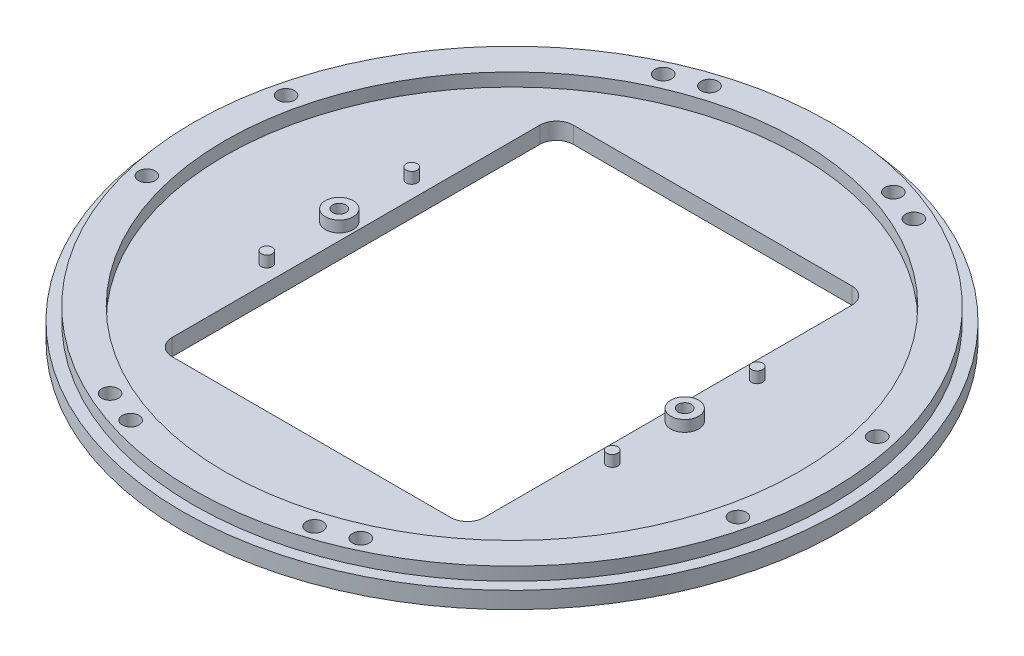
SolidWorks part; units mm, degrees
material "6061 合金"
ref_plane "前视基准面" through (0, 0, 0) normal (0, 0, 1) x (1, 0, 0)
ref_plane "上视基准面" through (0, 0, 0) normal (0, 1, 0) x (1, 0, 0)
ref_plane "右视基准面" through (0, 0, 0) normal (1, 0, 0) x (0, 0, -1)
sketch "草图1" plane through (0, 0, 0) normal (0, 0, 1) x (1, 0, 0)
  line L0 (0, 0) -> (-26746.8927, 0) construction
  line L1 (0, 0) -> (0, 26746.8927) construction
  line L2 (51.5, 2.35) -> (51.5, -3)
  line L3 (51.5, -3) -> (59.15, -3)
  line L4 (59.15, -3) -> (59.15, 0)
  line L5 (59.15, 0) -> (57.15, 0)
  line L6 (57.15, 0) -> (57.15, 2.35)
  line L7 (57.15, 2.35) -> (51.5, 2.35)
  dimension "D1" = 114.3
  dimension "D2" = 2
  dimension "D3" = 3
  dimension "D4" = 2.35
  dimension "D5" = 103
revolve "旋转1" add sketch "草图1" angle 360 about L1
sketch "草图3" plane through (0, 2.35, 0) normal (0, 1, 0) x (1, 0, 0)
  line L0 (0, -0.8566) -> (0, -50000.8566) construction
  line L1 (0, 0) -> (-50000, 0) construction
  line L2 (-22.5, 49.6387) -> (-22.5, -49.6387) construction
  line L3 (-16.5, 51.9423) -> (-16.5, -51.9423) construction
  circle A0 centre (0, 0) radius 54.5 construction
  circle A1 centre (-16.5, -51.9423) radius 1.5
  circle A2 centre (-22.5, -49.6387) radius 1.5
  circle A3 centre (-22.5, 49.6387) radius 1.5
  circle A4 centre (-16.5, 51.9423) radius 1.5
  circle A5 centre (16.5, 51.9423) radius 1.5
  circle A6 centre (22.5, 49.6387) radius 1.5
  circle A7 centre (22.5, -49.6387) radius 1.5
  circle A8 centre (16.5, -51.9423) radius 1.5
  point P10 (-22.5, 0)
  point P13 (-16.5, 0)
  dimension "D1" = 109
  dimension "D4" = 3
  dimension "D2" = 22.5
  dimension "D3" = 6
extrude "切除-拉伸1" cut sketch "草图3" against normal through all
sketch "草图2" plane through (0, -3, 0) normal (0, -1, 0) x (1, 0, 0)
  line L0 (0, 0) -> (0, 50000) construction
  line L1 (0, 0) -> (-50000, 0) construction
  line L2 (-28, 36) -> (-28, -36)
  line L3 (28, 36) -> (28, -36)
  line L4 (-28, 36) -> (28, 36)
  line L5 (-28, -36) -> (28, -36)
  circle A0 centre (0, 0) radius 51.5 construction
  circle A1 centre (0, 0) radius 51.5
  circle A3 centre (0, 0) radius 44 construction
  point P57 (0, 0)
  dimension "D4" = 36
  dimension "D2" = 88
  dimension "D1" = 28
extrude "凸台-拉伸1" add sketch "草图2" against normal blind 3
sketch "草图4" plane through (0, 0, 0) normal (0, 1, 0) x (1, 0, 0)
  line L0 (0.4768, 0) -> (50000.4768, 0) construction
  line L1 (0, -0.6791) -> (0, -50000.6791) construction
  circle A0 centre (0, 0) radius 50.1 construction
  circle A1 centre (45, 0) radius 5.1 construction
  circle A2 centre (45, 0) radius 5.7 construction
  circle A3 centre (0, 0) radius 39.3 construction
  circle A4 centre (31, -13) radius 1
  circle A6 centre (-31, -13) radius 1
  circle A7 centre (-31, 13) radius 1
  circle A8 centre (31, 13) radius 1
  circle A9 centre (31, 0) radius 2.5
  circle A10 centre (-31, 0) radius 2.5
  dimension "D1" = 100.2
  dimension "D2" = 10.2
  dimension "D3" = 11.4
  dimension "D4" = 2
  dimension "D5" = 31
  dimension "D6" = 13
  dimension "D7" = 5
  dimension "D8" = 78.6
extrude "凸台-拉伸2" add sketch "草图4" along normal blind 2
sketch "草图5" plane through (0, 2, 0) normal (0, 1, 0) x (1, 0, 0)
  circle A0 centre (31, 0) radius 1.2
  circle A1 centre (-31, 0) radius 1.2
  dimension "D1" = 2.4
extrude "切除-拉伸2" cut sketch "草图5" against normal through all
cosmetic thread "装饰螺纹线1" parameters "D1"=5, "D2"=3
cosmetic thread "装饰螺纹线2" parameters "D1"=5, "D2"=3
sketch "草图6" plane through (0, 0, 0) normal (0, 0, 1) x (1, 0, 0)
  line L0 (0, 0) -> (0, -39.9563) construction
  line L1 (57.15, 0) -> (-57.15, 0) construction
  line L2 (-32, -3) -> (-32, -20.2648) construction
  line L3 (-59.15, -3) -> (59.15, -3) construction
  line L4 (30.5, -3) -> (30.5, -25.0635) construction
  line L5 (-32, -3) -> (-32, -11)
  line L6 (-32, -11) -> (-52, -11)
  line L7 (-52, -11) -> (-59.15, -6)
  line L8 (-59.15, -6) -> (-59.15, -3)
  line L9 (-59.15, -3) -> (-32, -3)
  line L10 (30.5, -11) -> (50.5, -11)
  line L11 (50.5, -11) -> (59.15, -6)
  line L12 (59.15, -6) -> (59.15, -3)
  line L13 (59.15, -3) -> (30.5, -3)
  line L14 (30.5, -3) -> (30.5, -11)
  dimension "D1" = 32
  dimension "D2" = 30.5
  dimension "D3" = 8
  dimension "D4" = 3
  dimension "D5" = 20
sketch "草图8" plane through (0, 0, 0) normal (1, 0, 0) x (0, 0, -1)
  line L0 (0, 0) -> (0, -8.5) construction
  line L1 (59.15, 0) -> (-59.15, 0) construction
  line L2 (-59.15, -3) -> (59.15, -3) construction
  circle A0 centre (0, -8.5) radius 1.6
  dimension "D1" = 5.5
  dimension "D2" = 3.2
sketch "草图9" plane through (0, -3, 0) normal (0, -1, 0) x (1, 0, 0)
  circle A0 centre (-31, 0) radius 1.2 construction
  circle A1 centre (31, 0) radius 1.2 construction
  circle A2 centre (-31, 0) radius 1.2
  circle A3 centre (31, 0) radius 1.2
sketch "草图14" plane through (0, 0, 0) normal (0, 1, 0) x (1, 0, 0)
  line L0 (35.5031, -5.3746) -> (35.5031, 4.6254) construction
  circle A0 centre (35.5031, -5.3746) radius 2.5
  circle A1 centre (35.5031, 4.6254) radius 2.5
  circle A2 centre (35.5031, -0.3746) radius 2.5
  dimension "D1" = 5
fillet "圆角2" radius 3 4 edges at (-28, -1.5, 36) (28, -1.5, 36) (28, -1.5, -36) (-28, -1.5, -36)
sketch "草图11" plane through (0, -3, 0) normal (0, -1, 0) x (1, 0, 0)
  line L0 (0, 0) -> (-50000, 0) construction
  line L1 (0, 0) -> (0, 50000) construction
  circle A0 centre (0, 0) radius 54.5 construction
  circle A1 centre (-53.0471, 12.5) radius 1.5
  circle A2 centre (-53.0471, 12.5) radius 3 construction
  circle A3 centre (-40.0156, 37) radius 1.5 construction
  circle A5 centre (53.0471, 12.5) radius 1.5
  circle A7 centre (53.0471, -12.5) radius 1.5
  circle A10 centre (-53.0471, -12.5) radius 1.5
  dimension "D1" = 109
  dimension "D2" = 6
  dimension "D3" = 12.5
  dimension "D4" = 3
  dimension "D5" = 37
extrude "切除-拉伸6" cut sketch "草图11" against normal through all
